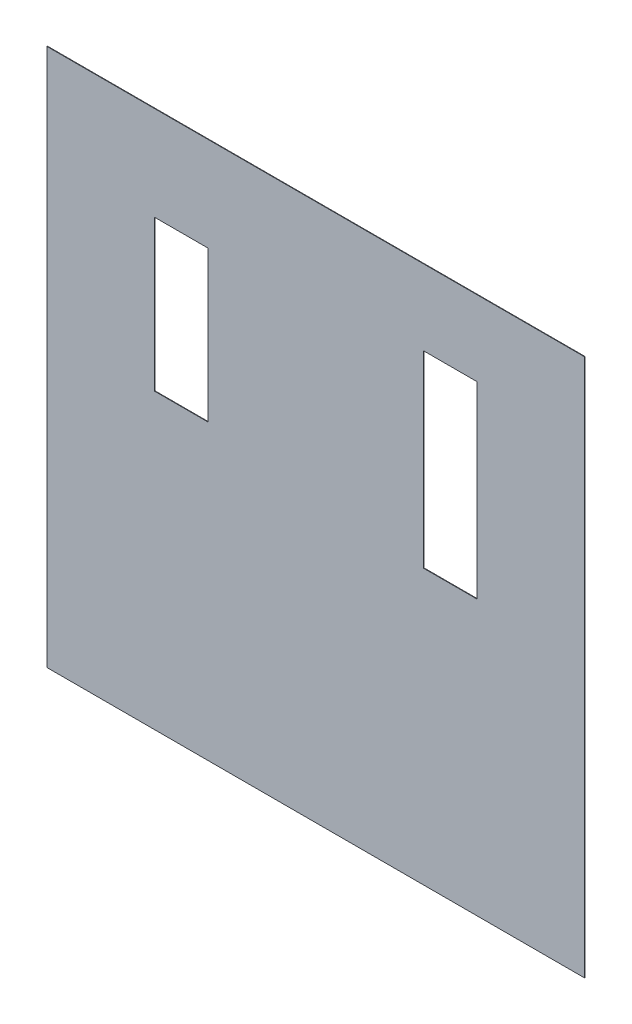
SolidWorks part; units mm, degrees
material "Custom Plastic"
ref_plane "Front Plane" through (0, 0, 0) normal (0, 0, 1) x (1, 0, 0)
ref_plane "Top Plane" through (0, 0, 0) normal (0, 1, 0) x (1, 0, 0)
ref_plane "Right Plane" through (0, 0, 0) normal (1, 0, 0) x (0, 0, -1)
sketch "Sketch1" plane through (0, 0, 0) normal (0, 0, 1) x (1, 0, 0)
  line L1 (0, 0) -> (25.4, 0)
  line L2 (0, 0) -> (0, 25.4)
  line L3 (0, 25.4) -> (25.4, 25.4)
  line L4 (25.4, 0) -> (25.4, 25.4)
  dimension "D1" = 25.4
  dimension "D2" = 25.4
extrude "Boss-Extrude1" add sketch "Sketch1" along normal blind 0.0254
sketch "Sketch2" plane through (0, 0, 0.0254) normal (0, 0, 1) x (1, 0, 0)
  line L0 (25.4, 25.4) -> (0, 25.4) construction
  line L1 (5.08, 20.955) -> (7.62, 20.955)
  line L2 (5.08, 20.955) -> (5.08, 13.843)
  line L3 (5.08, 13.843) -> (7.62, 13.843)
  line L4 (7.62, 20.955) -> (7.62, 13.843)
  line L5 (17.78, 21.844) -> (20.32, 21.844)
  line L6 (17.78, 21.844) -> (17.78, 12.954)
  line L7 (17.78, 12.954) -> (20.32, 12.954)
  line L8 (20.32, 21.844) -> (20.32, 12.954)
  point P10 (19.05, 12.954)
  point P11 (6.35, 13.843)
  point P12 (6.35, 20.955)
  point P13 (12.7, 25.4)
  dimension "D1" = 2.54
  dimension "D2" = 2.54
  dimension "D3" = 8.89
  dimension "D4" = 7.112
  dimension "D5" = 3.556
  dimension "D6" = 4.445
  dimension "D7" = 12.7
  dimension "D8" = 6.35
extrude "Cut-Extrude1" cut sketch "Sketch2" against normal through all
